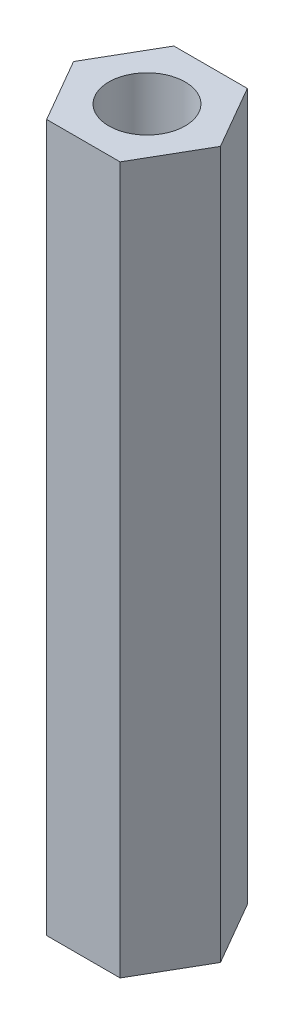
SolidWorks part; units mm, degrees
ref_plane "Front Plane" through (0, 0, 0) normal (0, 0, 1) x (1, 0, 0)
ref_plane "Top Plane" through (0, 0, 0) normal (0, 1, 0) x (1, 0, 0)
ref_plane "Right Plane" through (0, 0, 0) normal (1, 0, 0) x (0, 0, -1)
sketch "Sketch1" plane through (0, 0, 0) normal (0, 1, 0) x (1, 0, 0)
  line L1 (-1.299, -2.25) -> (1.299, -2.25)
  line L2 (1.299, -2.25) -> (2.5981, 0)
  line L3 (2.5981, 0) -> (1.299, 2.25)
  line L4 (1.299, 2.25) -> (-1.299, 2.25)
  line L5 (-1.299, 2.25) -> (-2.5981, 0)
  line L6 (-2.5981, 0) -> (-1.299, -2.25)
  circle A0 centre (0, 0) radius 1.35
  circle A1 centre (0, 0) radius 2.25 construction
  dimension "D1" = 2.7
  dimension "D2" = 4.5
extrude "Boss-Extrude1" add sketch "Sketch1" along normal blind 25
